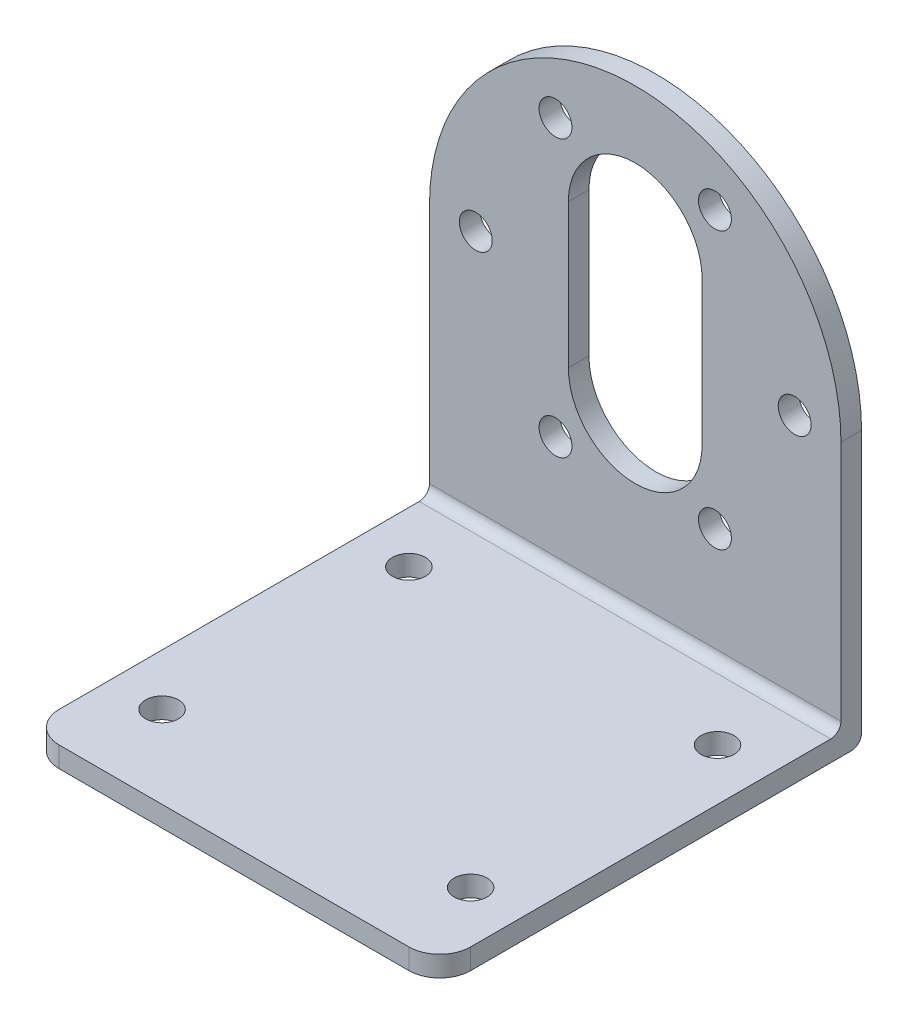
SolidWorks part; units mm, degrees
ref_plane "前视基准面" through (0, 0, 0) normal (0, 0, 1) x (1, 0, 0)
ref_plane "上视基准面" through (0, 0, 0) normal (0, 1, 0) x (1, 0, 0)
ref_plane "右视基准面" through (0, 0, 0) normal (1, 0, 0) x (0, 0, -1)
sketch "草图1" plane through (0, 0, 0) normal (0, 1, 0) x (1, 0, 0)
  line L1 (-20, 20.5) -> (20, 20.5)
  line L2 (-20, 20.5) -> (-20, -20.5)
  line L3 (-20, -20.5) -> (20, -20.5)
  line L4 (20, 20.5) -> (20, -20.5)
  line L5 (-20, 20.5) -> (20, -20.5) construction
  line L6 (-20, -20.5) -> (20, 20.5) construction
  point P0 (0, 0)
  dimension "D1" = 41
  dimension "D2" = 40
extrude "凸台-拉伸1" add sketch "草图1" along normal blind 2
fillet "圆角1" radius 3 2 edges at (20, 1, 20.5) (-20, 1, 20.5)
sketch "草图2" plane through (0, 2, 0) normal (0, 1, 0) x (1, 0, 0)
  line L0 (0, 29.7294) -> (0, -54.9977) construction
  line L1 (-17, -20.5) -> (17, -20.5) construction
  circle A0 centre (-15, -12.5) radius 1.6
  circle A1 centre (-15, 11.5) radius 1.6
  circle A2 centre (15, 11.5) radius 1.6
  circle A3 centre (15, -12.5) radius 1.6
  dimension "D1" = 3.2
  dimension "D2" = 15
  dimension "D3" = 15
  dimension "D4" = 15
  dimension "D5" = 15
  dimension "D6" = 8
  dimension "D7" = 8
  dimension "D8" = 24
  dimension "D9" = 24
extrude "切除-拉伸1" cut sketch "草图2" against normal blind 50
sketch "草图3" plane through (0, 0, -20.5) normal (0, 0, -1) x (-1, 0, 0)
  line L0 (0, 61.3868) -> (0, -44.9697) construction
  line L1 (20, 2) -> (20, 0) construction
  line L2 (-20, 0) -> (20, 0)
  line L3 (-20, 0) -> (-20, 26.5)
  line L5 (20, 0) -> (20, 26.5)
  arc A0 (20, 26.5) -> (-20, 26.5) centre (0, 26.5) ccw
  dimension "D1" = 26.5
extrude "凸台-拉伸2" add sketch "草图3" against normal blind 2
sketch "草图4" plane through (0, 0, -20.5) normal (0, 0, -1) x (-1, 0, 0)
  line L0 (0, 60.0344) -> (0, -24.6769) construction
  line L1 (0, 33.5) -> (0, 19.5) construction
  line L2 (6.5, 33.5) -> (6.5, 19.5)
  line L3 (-6.5, 33.5) -> (-6.5, 19.5)
  arc A0 (6.5, 33.5) -> (-6.5, 33.5) centre (0, 33.5) ccw
  arc A1 (-6.5, 19.5) -> (6.5, 19.5) centre (0, 19.5) ccw
  arc A2 (20, 26.5) -> (-20, 26.5) centre (0, 26.5) ccw construction
  point P6 (0, 26.5)
  point P11 (0, 0)
  point P12 (0, 0)
  point P13 (0, 0)
  dimension "D1" = 6.5
  dimension "D2" = 14
extrude "切除-拉伸2" cut sketch "草图4" against normal blind 50
sketch "草图5" plane through (0, 0, -20.5) normal (0, 0, -1) x (-1, 0, 0)
  circle A0 centre (0, 26.5) radius 15.5 construction
  circle A1 centre (15.5, 26.5) radius 1.6
  dimension "D1" = 31
  dimension "D2" = 3.2
extrude "切除-拉伸3" cut sketch "草图5" against normal blind 50
pattern_circular "阵列(圆周)1" count 6 over 360 about axis through (0, 26.5, 0) along (0, 0, 1) of "切除-拉伸3"
fillet "圆角2" radius 1 1 edges at (0, 0, -20.5)
fillet "圆角3" radius 1 1 edges at (0, 2, -18.5)
